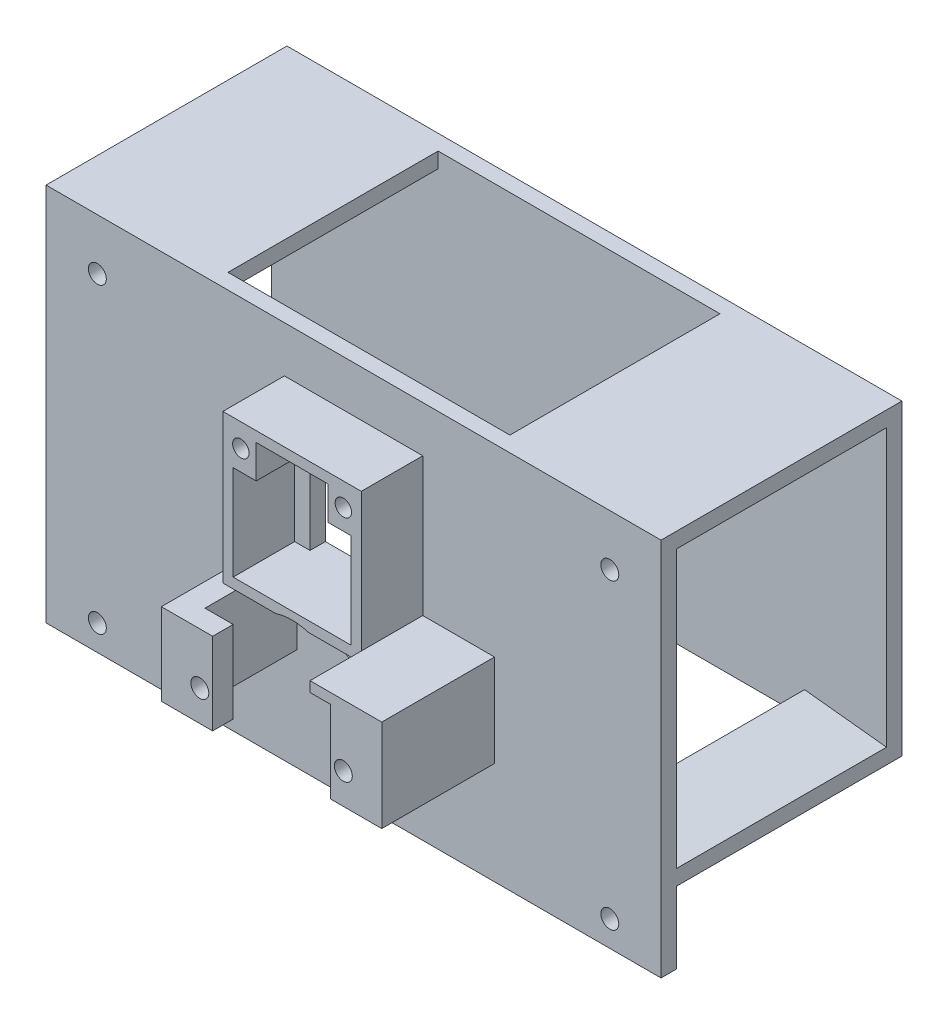
SolidWorks part; units mm, degrees
ref_plane "前视基准面" through (0, 0, 0) normal (0, 0, 1) x (1, 0, 0)
ref_plane "上视基准面" through (0, 0, 0) normal (0, 1, 0) x (1, 0, 0)
ref_plane "右视基准面" through (0, 0, 0) normal (1, 0, 0) x (0, 0, -1)
sketch "草图1" plane through (0, 0, 0) normal (0, 0, -1) x (1, 0, 0)
  line L4 (-60, 30) -> (60, -30) construction
  line L5 (-60, -30) -> (60, -30)
  line L6 (-60, -30) -> (-60, 30)
  line L7 (-60, 30) -> (60, 30)
  line L8 (60, -30) -> (60, 30)
  dimension "D1" = 120
  dimension "D2" = 60
extrude "凸台-拉伸1" add sketch "草图1" along normal blind 47
shell "抽壳2" thickness 3
sketch "草图2" plane through (0, 30, 45) normal (0, -1, 0) x (-1, 0, 0)
  line L0 (0, 92) -> (0, 68.5) construction
  line L1 (-60, 92) -> (60, 92) construction
  line L2 (0, 68.5) -> (-60, 68.5) construction
  line L5 (-60, 92) -> (-60, 45) construction
  line L6 (60, 89) -> (-60, 89) construction
  line L7 (-27.5, 89) -> (27.5, 89)
  line L8 (-27.5, 89) -> (-27.5, 48)
  line L9 (-27.5, 48) -> (27.5, 48)
  line L10 (27.5, 89) -> (27.5, 48)
  line L11 (-27.5, 89) -> (27.5, 48) construction
  line L12 (-27.5, 48) -> (27.5, 89) construction
  point P15 (-60, 68.5)
  dimension "D2" = 55
extrude "切除-拉伸1" cut sketch "草图2" along normal up to surface (3 mm away) up to face at (0, 27, -23.5)
sketch "草图5" plane through (0, -30, 0) normal (0, -1, 0) x (1, 0, 0)
  line L0 (0, 0) -> (0, -23.5) construction
  line L1 (-44, -44) -> (44, -44)
  line L2 (-44, -44) -> (-44, -3)
  line L3 (-44, -3) -> (44, -3)
  line L4 (44, -44) -> (44, -3)
  line L5 (-44, -44) -> (44, -3) construction
  line L6 (-44, -3) -> (44, -44) construction
  line L7 (60, 0) -> (-60, 0) construction
  line L8 (0, -23.5) -> (-60, -23.5) construction
  line L9 (-60, -47) -> (-60, 0) construction
  line L11 (27.5, -3) -> (60, -3) construction
  point P0 (0, -23.5)
  dimension "D1" = 88
extrude "切除-拉伸3" cut sketch "草图5" against normal blind 10
sketch "草图6" plane through (0, 0, 0) normal (0, 0, 1) x (1, 0, 0)
  line L6 (0, 30) -> (0, -18) construction
  line L8 (-60, 30) -> (60, 30) construction
  line L9 (27.5, 27) -> (60, 27) construction
  circle A1 centre (0, -18) radius 2.5
  dimension "D1" = 5
  dimension "D2" = 45
  dimension "D3" = 48
extrude "切除-拉伸4" cut sketch "草图6" against normal through all
sketch "草图8" plane through (0, 0, -44) normal (0, 0, -1) x (-1, 0, 0)
  line L0 (-60, -27) -> (-44, -25.2705)
  line L1 (-44, -25.2705) -> (-44, -30)
  line L2 (-60, -30) -> (60, -30) construction
  line L3 (-44, -30) -> (-60, -30)
  line L4 (-60, -30) -> (-60, -27)
  line L6 (-60, 30) -> (-60, -30) construction
  line L7 (-44, -27) -> (-44, -30) construction
  circle A0 centre (0, -18) radius 1.3759 construction
  circle A1 centre (0, -18) radius 2.5 construction
extrude "凸台-拉伸4" add sketch "草图8" against normal up to surface (41 mm away)
mirror "镜向1" about plane through (0, 0, 0) normal (1, 0, 0) of "凸台-拉伸4"
sketch "草图9" plane through (0, 0, 0) normal (0, 0, 1) x (1, 0, 0)
  line L0 (0, 6.5) -> (0, 30) construction
  line L1 (-8.5, 19) -> (8.5, 19)
  line L2 (-8.5, 19) -> (-8.5, -6)
  line L3 (-8.5, -6) -> (8.5, -6)
  line L4 (8.5, 19) -> (8.5, -6)
  line L5 (-8.5, 19) -> (8.5, -6) construction
  line L6 (-8.5, -6) -> (8.5, 19) construction
  line L7 (-60, 30) -> (60, 30) construction
  point P0 (0, 6.5)
  dimension "D1" = 17
  dimension "D2" = 25
  dimension "D3" = 11
extrude "切除-拉伸5" cut sketch "草图9" against normal up to next
sketch "草图10" plane through (0, 0, 0) normal (0, 0, 1) x (1, 0, 0)
  line L0 (0, -6) -> (0, -8) construction
  line L5 (-13.5, 21) -> (13.5, 21)
  line L6 (-8.5, 19) -> (8.5, 19) construction
  line L12 (-8.5, -6) -> (8.5, -6) construction
  line L13 (-11.5, -6) -> (11.5, -6)
  line L14 (-10, 16.5) -> (10, 16.5) construction
  line L24 (7, 19) -> (7, 12.5)
  line L25 (-7, 19) -> (-7, 12.5)
  line L27 (-13.5, 21) -> (-13.5, -8)
  line L30 (13.5, 21) -> (13.5, -8)
  line L31 (13.5, -8) -> (-13.5, -8)
  line L34 (-7, 19) -> (7, 19)
  line L40 (-7, 12.5) -> (-11.5, 12.5)
  line L41 (-11.5, 12.5) -> (-11.5, -6)
  line L43 (7, 12.5) -> (11.5, 12.5)
  line L44 (11.5, 12.5) -> (11.5, -6)
  line L45 (-11.5, 1) -> (-11.5, 12.5) construction
  circle A1 centre (-10, 16.5) radius 1.6
  circle A3 centre (10, 16.5) radius 1.6
  point P0 (0, 6.5)
  point P5 (0, 6.5)
  point P10 (0, 16.5)
  dimension "D3" = 3.2
  dimension "D4" = 20
  dimension "D2" = 2
  dimension "D5" = 8.5
  dimension "D6" = 4.5
  dimension "D7" = 2
  dimension "D8" = 3
  dimension "D9" = 2
  dimension "D10" = 2
  dimension "D11" = 27
  dimension "D14" = 14
extrude "凸台-拉伸5" add sketch "草图10" along normal blind 12
sketch "草图14" plane through (0, 0, 0) normal (0, 0, 1) x (1, 0, 0)
  line L0 (-5.5, -16) -> (17.5, -16) construction
  line L1 (-15.5, -8) -> (-5.5, -8)
  line L2 (-15.5, -8) -> (-15.5, -24)
  line L3 (-15.5, -24) -> (-5.5, -24)
  line L4 (-5.5, -8) -> (-5.5, -24)
  line L5 (17.5, -8) -> (27.5, -8)
  line L6 (17.5, -8) -> (17.5, -24)
  line L7 (17.5, -24) -> (27.5, -24)
  line L8 (27.5, -8) -> (27.5, -24)
  line L9 (-8, -18) -> (0, -18) construction
  line L10 (6, -16) -> (6, -23.5101) construction
  line L11 (-13.5, -8) -> (13.5, -8) construction
  circle A1 centre (-8, -18) radius 1.75
  circle A2 centre (20, -18) radius 1.75
  dimension "D5" = 3.5
  dimension "D1" = 8
  dimension "D2" = 28
  dimension "D3" = 23
  dimension "D4" = 10
  dimension "D6" = 6
extrude "凸台-拉伸7" add sketch "草图14" along normal blind 22
sketch "草图15" plane through (0, 0, 0) normal (0, 0, 1) x (1, 0, 0)
  circle A0 centre (0, -18) radius 10.5
  dimension "D1" = 21
extrude "切除-拉伸7" cut sketch "草图15" along normal blind 12
sketch "草图17" plane through (0, 0, 12) normal (0, 0, -1) x (-1, 0, 0)
  line L5 (5.5, -9.0557) -> (5.5, -24)
  line L6 (5.5, -24) -> (8.6168, -24)
  line L9 (5.5, -9.0557) -> (5.5, -24)
  line L10 (5.5, -24) -> (8.6168, -24)
  arc A1 (8.6168, -24) -> (5.5, -9.0557) centre (0, -18) ccw
  arc A6 (8.6168, -24) -> (5.5, -9.0557) centre (0, -18) ccw
  dimension "D1" = 0
extrude "切除-拉伸8" cut sketch "草图17" against normal offset from surface (6 mm away) 4 up to face at (-10.5, -16, 22)
sketch "草图19" plane through (0, 0, 0) normal (0, 0, 1) x (1, 0, 0)
  line L0 (-15.5, -24) -> (-8.6168, -24) construction
  line L1 (-11, -24) -> (23, -24)
  line L2 (-11, -24) -> (-11, -8)
  line L3 (-11, -8) -> (23, -8)
  line L4 (23, -24) -> (23, -8)
  line L6 (3.2016, -8) -> (13.5, -8) construction
  line L8 (-8, -18) -> (20, -18) construction
  line L9 (6, -18) -> (6, -24) construction
  dimension "D1" = 34
extrude "切除-拉伸9" cut sketch "草图19" along normal up to surface (18 mm away) up to face at (-6.25, -18, 18)
sketch "草图16" plane through (0, 0, 0) normal (0, 0, 1) x (1, 0, 0)
  line L5 (13.5, -8) -> (27.5, -8)
  line L6 (13.5, -8) -> (13.5, -6)
  line L7 (13.5, -6) -> (27.5, -6)
  line L8 (27.5, -8) -> (27.5, -6)
  line L10 (27.5, -24) -> (27.5, -8) construction
  line L12 (-11.5, -6) -> (11.5, -6) construction
  point P2 (0, 0)
  point P3 (0, 0)
  point P11 (0, 0)
  point P12 (13.5, -8)
  point P13 (0, 0)
  point P14 (0, 0)
  point P17 (0, 0)
  point P18 (-13.5, 1.5008)
extrude "凸台-拉伸8" add sketch "草图16" along normal up to surface (22 mm away) up to face at (-10.5, -16, 22)
sketch "草图20" plane through (0, 0, -3) normal (0, 0, -1) x (-1, 0, 0)
  line L1 (-13, 19.5) -> (-7, 19.5)
  line L2 (-13, 19.5) -> (-13, 13.5)
  line L3 (-13, 13.5) -> (-7, 13.5)
  line L4 (-7, 19.5) -> (-7, 13.5)
  line L5 (-13, 19.5) -> (-7, 13.5) construction
  line L6 (-13, 13.5) -> (-7, 19.5) construction
  line L7 (13, 19.5) -> (7, 19.5)
  line L8 (13, 19.5) -> (13, 13.5)
  line L9 (13, 13.5) -> (7, 13.5)
  line L10 (7, 19.5) -> (7, 13.5)
  line L11 (13, 19.5) -> (7, 13.5) construction
  line L12 (13, 13.5) -> (7, 19.5) construction
  circle A4 centre (-10, 16.5) radius 1.6 construction
  circle A5 centre (10, 16.5) radius 1.6 construction
  point P0 (-10, 16.5)
  point P5 (10, 16.5)
  dimension "D2" = 6
extrude "切除-拉伸10" cut sketch "草图20" against normal offset from surface (5 mm away) 10 up to face at (-8.4, 16.5, 12)
sketch "草图21" plane through (0, -30, 0) normal (0, -1, 0) x (1, 0, 0)
  line L0 (60, -47) -> (60, 0) construction
  line L1 (-60, 0) -> (60, 0)
  line L2 (-60, 0) -> (-60, -3)
  line L3 (-60, -3) -> (60, -3)
  line L4 (60, 0) -> (60, -3)
  line L5 (44, -3) -> (-44, -3) construction
extrude "凸台-拉伸9" add sketch "草图21" along normal blind 14
sketch "草图11" plane through (0, 0, 0) normal (0, 0, -1) x (-1, 0, 0)
  line L0 (0, 30) -> (0, -30) construction
  line L1 (60, 30) -> (-60, 30) construction
  line L2 (-60, -30) -> (60, -30) construction
  line L3 (60, -44) -> (-60, -44) construction
  circle A0 centre (-50, 20) radius 1.75
  circle A1 centre (50, 20) radius 1.75
  circle A2 centre (-50, -39) radius 1.75
  circle A3 centre (50, -39) radius 1.75
  dimension "D1" = 3.5
  dimension "D2" = 100
  dimension "D3" = 10
  dimension "D4" = 5
  dimension "D5" = 59
extrude "切除-拉伸6" cut sketch "草图11" along normal through all
